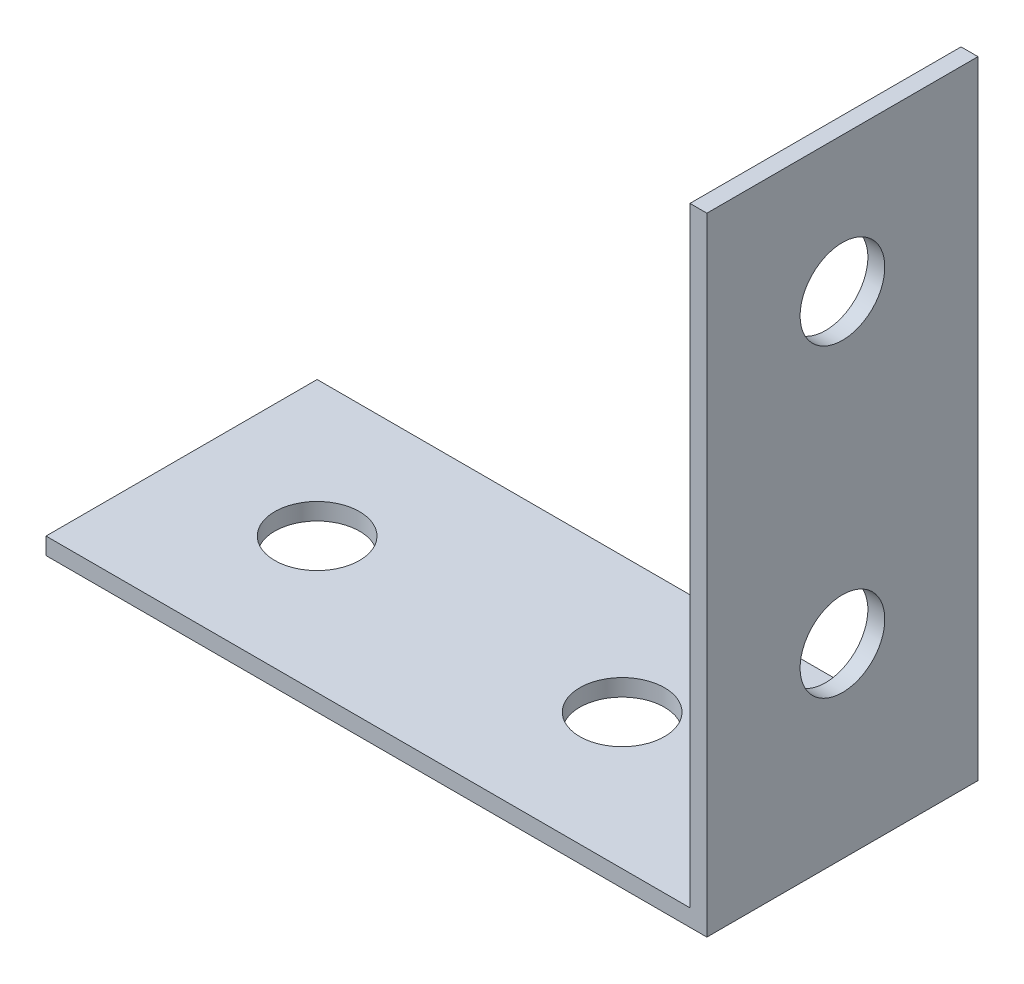
SolidWorks part; units mm, degrees
ref_plane "前基準面" through (0, 0, 0) normal (0, 0, 1) x (1, 0, 0)
ref_plane "上基準面" through (0, 0, 0) normal (0, 1, 0) x (1, 0, 0)
ref_plane "右基準面" through (0, 0, 0) normal (1, 0, 0) x (0, 0, -1)
sketch "草圖1" plane through (0, 0, 0) normal (0, 1, 0) x (1, 0, 0)
  line L1 (-19, 8) -> (19, 8)
  line L2 (-19, 8) -> (-19, -8)
  line L3 (-19, -8) -> (19, -8)
  line L4 (19, 8) -> (19, -8)
  line L5 (-19, 8) -> (19, -8) construction
  line L6 (-19, -8) -> (19, 8) construction
  point P0 (0, 0)
  dimension "D1" = 38
  dimension "D2" = 16
extrude "填料-伸長1" add sketch "草圖1" along normal blind 1
sketch "草圖2" plane through (19, 0, 0) normal (1, 0, 0) x (0, 0, -1)
  line L0 (8, 1) -> (8, 0) construction
  line L1 (-8, 0) -> (8, 0)
  line L2 (-8, 0) -> (-8, 37)
  line L3 (-8, 37) -> (8, 37)
  line L4 (8, 0) -> (8, 37)
  dimension "D1" = 37
extrude "填料-伸長2" add sketch "草圖2" along normal blind 1
sketch "草圖3" plane through (0, 1, 0) normal (0, 1, 0) x (1, 0, 0)
  line L0 (-19, 8) -> (-19, -8) construction
  circle A0 centre (-11, 0) radius 2.5
  circle A1 centre (7, 0) radius 2.5
  dimension "D1" = 5
  dimension "D2" = 8
  dimension "D3" = 18
extrude "除料-伸長1" cut sketch "草圖3" against normal up to next
sketch "草圖4" plane through (19, 0, 0) normal (-1, 0, 0) x (0, 0, 1)
  line L0 (-8, 37) -> (8, 37) construction
  circle A0 centre (0, 29) radius 2.5
  circle A1 centre (0, 11) radius 2.5
  dimension "D1" = 5
  dimension "D2" = 8
  dimension "D3" = 18
extrude "除料-伸長2" cut sketch "草圖4" against normal up to next
